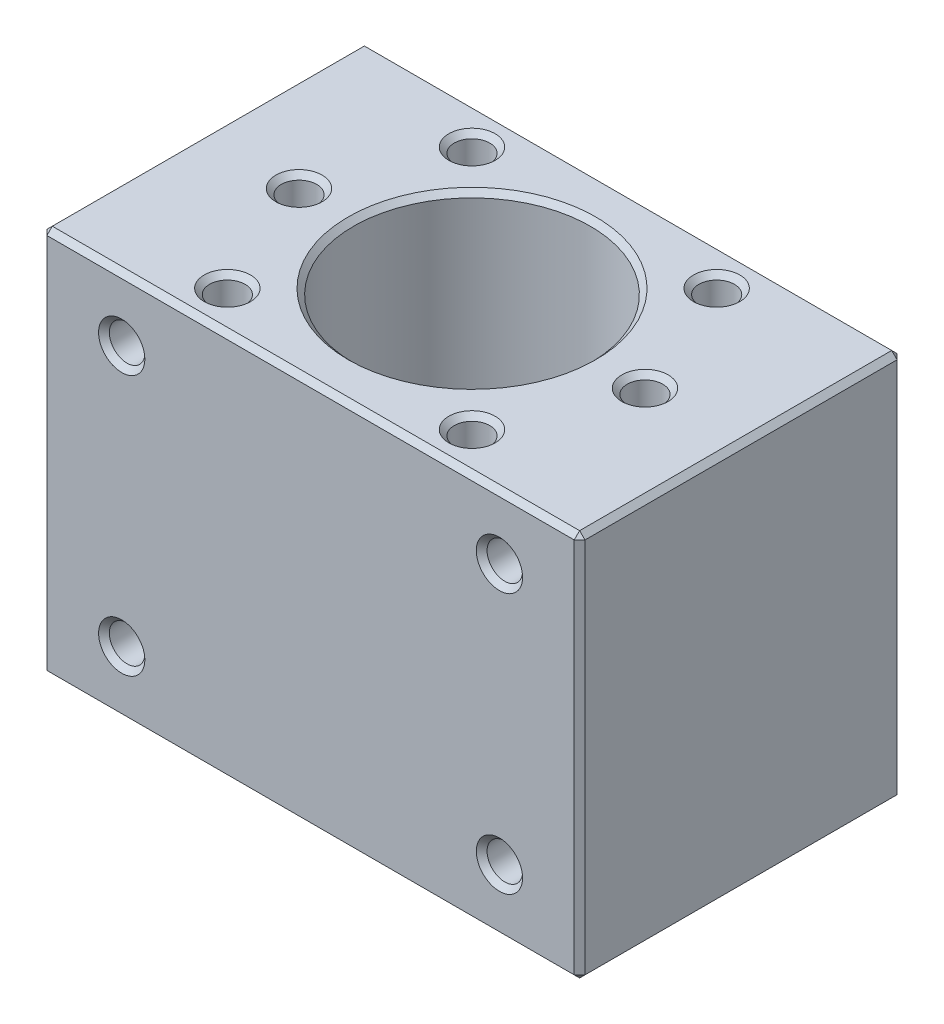
SolidWorks part; units mm, degrees
ref_plane "Front Plane" through (0, 0, 0) normal (0, 0, 1) x (1, 0, 0)
ref_plane "Top Plane" through (0, 0, 0) normal (0, 1, 0) x (1, 0, 0)
ref_plane "Right Plane" through (0, 0, 0) normal (1, 0, 0) x (0, 0, -1)
sketch "Sketch1" plane through (0, 0, 0) normal (0, 1, 0) x (1, 0, 0)
  line L0 (0, 30) -> (50, 0) construction
  line L1 (0, 0) -> (50, 0)
  line L2 (0, 0) -> (0, 30)
  line L3 (0, 30) -> (50, 30)
  line L4 (50, 0) -> (50, 30)
  line L5 (0, 15) -> (50, 15) construction
  circle A0 centre (25, 15) radius 11
  circle A1 centre (41.075, 15) radius 1.65
  circle A2 centre (25, 15) radius 16.075 construction
  circle A3 centre (36.3667, 26.3667) radius 1.65
  circle A4 centre (25, 31.075) radius 1.65 construction
  circle A5 centre (13.6333, 26.3667) radius 1.65
  circle A6 centre (8.925, 15) radius 1.65
  circle A7 centre (13.6333, 3.6333) radius 1.65
  circle A8 centre (25, -1.075) radius 1.65 construction
  circle A9 centre (36.3667, 3.6333) radius 1.65
  point P28 (25, 15)
  dimension "D3" = 22
  dimension "D5" = 3.3
  dimension "D1" = 50
  dimension "D2" = 30
  dimension "D4" = 16.075
  dimension "D6" = 8
extrude "Boss-Extrude1" add sketch "Sketch1" against normal blind 36 contours L1 L4 L3 L2 A9 A7 A6 A5 A3 A1 A0 | A1 | A3 | A9 | A7 | A6 | A5
sketch "Sketch3" plane through (0, 0, 0) normal (0, 1, 0) x (1, 0, 0)
  circle A0 centre (36.3667, 26.3667) radius 1.65 construction
  circle A1 centre (41.075, 15) radius 1.65 construction
  circle A2 centre (36.3667, 3.6333) radius 1.65 construction
  circle A3 centre (13.6333, 3.6333) radius 1.65 construction
  circle A4 centre (8.925, 15) radius 1.65 construction
  circle A5 centre (13.6333, 26.3667) radius 1.65 construction
  circle A6 centre (36.3667, 26.3667) radius 1.65
  circle A7 centre (41.075, 15) radius 1.65
  circle A8 centre (36.3667, 3.6333) radius 1.65
  circle A9 centre (13.6333, 3.6333) radius 1.65
  circle A10 centre (8.925, 15) radius 1.65
  circle A11 centre (13.6333, 26.3667) radius 1.65
hole_wizard "Tap Drill for M4x0.7 Tap1" positions "3DSketch2" profile "Sketch4" hole size "M4x0.7" standard "ANSI Metric"
sketch3d "3DSketch2"
  point P0 (8.925, 0, -15)
  point P3 (13.6333, 0, -26.3667)
  point P6 (36.3667, 0, -26.3667)
  point P9 (41.075, 0, -15)
  point P12 (36.3667, 0, -3.6333)
  point P15 (13.6333, 0, -3.6333)
sketch "Sketch4" plane through (8.925, 0, -15) normal (1, 0, 0) x (0, 0, 1)
  line L0 (0, 0) -> (0, 10.9914)
  line L1 (0, 10.9914) -> (1.65, 10)
  line L2 (1.65, 10) -> (1.65, 0)
  line L5 (1.65, 0) -> (0, 0)
  line L10 (0, 10.9914) -> (-1.65, 10) construction
  line L11 (0, -6.35) -> (0, 107.95) construction
  dimension "Hole Dia." = 3.3
  dimension "Hole Depth" = 10
  dimension "Drill Angle" = 118
sketch "Sketch5" plane through (0, 0, 0) normal (0, 0, 1) x (1, 0, 0)
  line L0 (25, -30.1) -> (25, -36) construction
  line L1 (7.45, -5.9) -> (42.55, -5.9) construction
  line L2 (7.45, -5.9) -> (7.45, -30.1) construction
  line L3 (7.45, -30.1) -> (42.55, -30.1) construction
  line L4 (42.55, -5.9) -> (42.55, -30.1) construction
  line L5 (0, -36) -> (50, -36) construction
  line L6 (42.55, -18) -> (50, -18) construction
  line L7 (50, -36) -> (50, 0) construction
  dimension "D1" = 24.2
  dimension "D2" = 35.1
hole_wizard "Tap Drill for M4x0.7 Tap2" positions "3DSketch3" profile "Sketch6" hole size "M4x0.7" standard "ANSI Metric"
sketch3d "3DSketch3"
  point P0 (7.45, -5.9, 0)
  point P3 (42.55, -5.9, 0)
  point P6 (42.55, -30.1, 0)
  point P9 (7.45, -30.1, 0)
sketch "Sketch6" plane through (7.45, -5.9, 0) normal (1, 0, 0) x (0, -1, 0)
  line L0 (0, 0) -> (0, 13.9914)
  line L1 (0, 13.9914) -> (1.65, 13)
  line L2 (1.65, 13) -> (1.65, 0)
  line L5 (1.65, 0) -> (0, 0)
  line L10 (0, 13.9914) -> (-1.65, 13) construction
  line L11 (0, -6.35) -> (0, 107.95) construction
  dimension "Hole Dia." = 3.3
  dimension "Hole Depth" = 13
  dimension "Drill Angle" = 118
chamfer "Chamfer1" distance 0.5 angle 45 24 edges at (9.1, -30.1, 0) (44.2, -30.1, 0) (44.2, -5.9, 0) (9.1, -5.9, 0) (25, -36, -4) (0, -18, -30) (50, -18, -30) (50, -18, 0) (50, -36, -15) (25, -36, -30) (0, -36, -15) (25, -36, 0) (0, -18, 0) (0, 0, -15) (25, 0, -30) (50, 0, -15) (25, 0, 0) (25, 0, -4) (13.6333, 0, -1.9833) (36.3667, 0, -1.9833) (41.075, 0, -13.35) (36.3667, 0, -24.7167) (13.6333, 0, -24.7167) (8.925, 0, -13.35)
